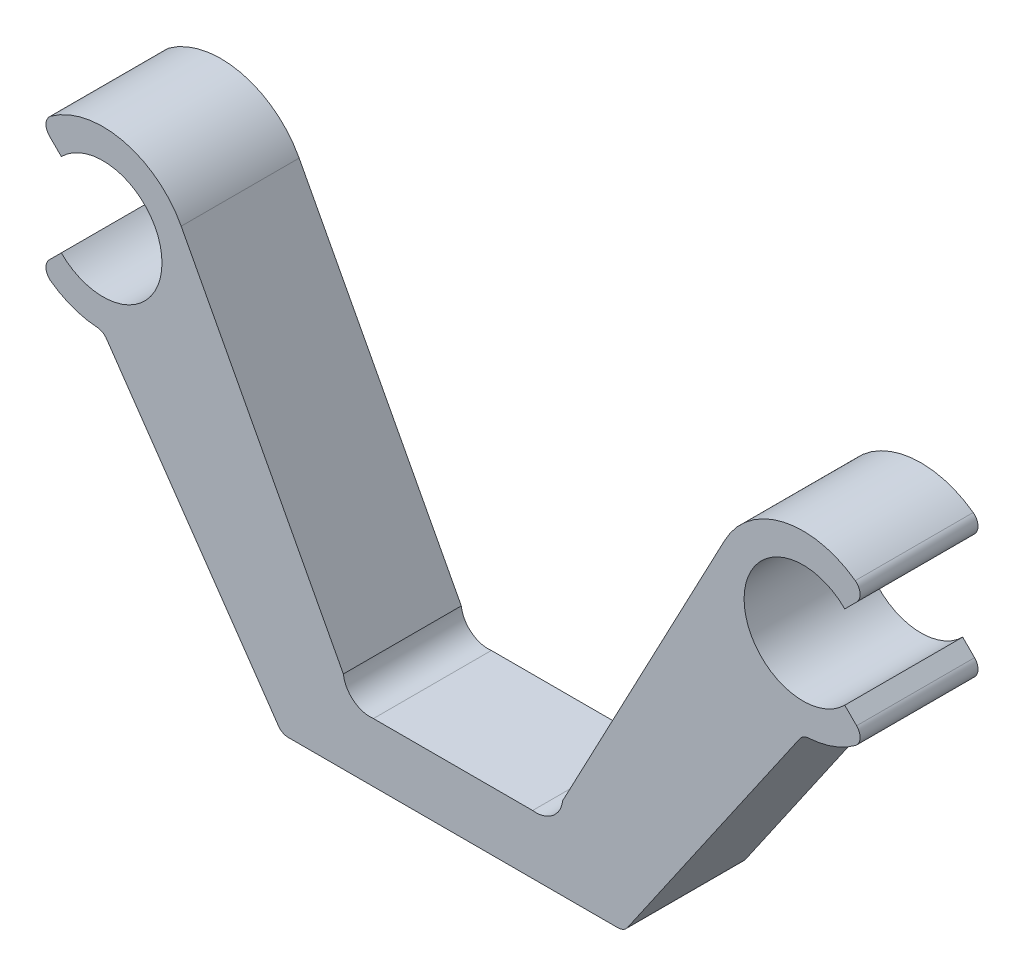
SolidWorks part; units mm, degrees
ref_plane "Front Plane" through (0, 0, 0) normal (0, 0, 1) x (1, 0, 0)
ref_plane "Top Plane" through (0, 0, 0) normal (0, 1, 0) x (1, 0, 0)
ref_plane "Right Plane" through (0, 0, 0) normal (1, 0, 0) x (0, 0, -1)
sketch "Sketch1" plane through (0, 0, 0) normal (0, 0, 1) x (1, 0, 0)
  line L0 (14.5, 0) -> (-14.5, 0)
  line L1 (0, 5) -> (0, 29.5) construction
  line L2 (-14.5, 0) -> (-14.5, 5) construction
  line L3 (6.75, 5) -> (-6.75, 5)
  line L4 (-14.5, 5) -> (-14.5, 7) construction
  line L5 (0, 7) -> (-9.2995, 7) construction
  line L6 (0, 29.5) -> (-21.1962, 29.5) construction
  line L7 (-14.5, 0) -> (-29.68, 22)
  line L8 (-9.2995, 7) -> (-23.0498, 33.0057)
  line L9 (-29.68, 29.5) -> (-29.68, 22) construction
  line L10 (-29.68, 29.5) -> (-34.9833, 24.1967)
  line L11 (-29.68, 29.5) -> (-34.9833, 34.8033)
  line L12 (-24.68, 29.5) -> (-29.68, 29.5) construction
  line L14 (9.2995, 7) -> (23.0498, 33.0057)
  line L15 (29.68, 29.5) -> (34.9833, 34.8033)
  line L16 (29.68, 29.5) -> (34.9833, 24.1967)
  line L17 (14.5, 0) -> (29.68, 22)
  arc A0 (-6.75, 5) -> (-9.2995, 7) centre (-7.0247, 7.2747) cw
  arc A1 (-34.9833, 24.1967) -> (-29.68, 22) centre (-29.68, 29.5) ccw
  arc A3 (-23.0498, 33.0057) -> (-34.9833, 34.8033) centre (-29.68, 29.5) ccw
  arc A4 (6.75, 5) -> (9.2995, 7) centre (7.0247, 7.2747) ccw
  arc A5 (23.0498, 33.0057) -> (34.9833, 34.8033) centre (29.68, 29.5) cw
  arc A6 (34.9833, 24.1967) -> (29.68, 22) centre (29.68, 29.5) cw
  dimension "15" = 15
  dimension "D3" = 5
  dimension "D4" = 6.75
  dimension "D5" = 2
  dimension "D6" = 9.2995
  dimension "D7" = 29.68
extrude "Boss-Extrude2" add sketch "Sketch1" along normal blind 10
ref_plane "Plane1" through (0, 0, 10) normal (0, 0, 1) x (1, 0, 0)
sketch "Sketch2" plane through (0, 0, 10) normal (0, 0, 1) x (1, 0, 0)
  circle A0 centre (-29.68, 29.5) radius 5
  circle A1 centre (29.68, 29.5) radius 5
  dimension "D1" = 10
  dimension "D2" = 10
extrude "Cut-Extrude1" cut sketch "Sketch2" against normal blind 10
sketch "Sketch3" plane through (0, 0, 0) normal (0, -1, 0) x (1, 0, 0)
  line L0 (0, 0) -> (0, 10) construction
  line L1 (20.35, 10) -> (-20.35, 10) construction
  line L2 (0, 5) -> (11.75, 5) construction
  line L3 (0, 5) -> (-11.75, 5) construction
  circle A0 centre (-11.75, 5) radius 1.35
  circle A1 centre (11.75, 5) radius 1.35
  dimension "D3" = 2.7
  dimension "D4" = 2.7
  dimension "D1" = 11.75
  dimension "D2" = 11.75
extrude "Cut-Extrude2" cut sketch "Sketch3" against normal blind 3
fillet "Fillet1" radius 1 2 edges at (-34.9833, 24.1967, 5) (-34.9833, 34.8033, 5)
fillet "Fillet2" radius 1 6 edges at (-29.68, 22, 5) (34.9833, 34.8033, 5) (29.68, 22, 5) (34.9833, 24.1967, 5) (14.5, 0, 5) (-14.5, 0, 5)
